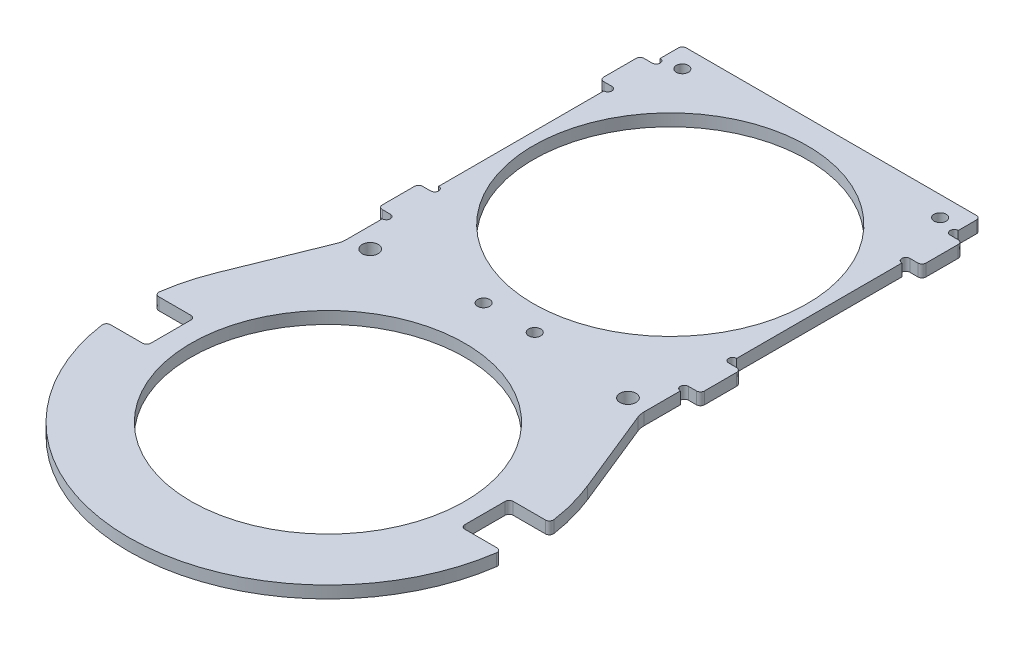
SolidWorks part; units mm, degrees
material "Thornel Mat VMA"
ref_plane "前视基准面" through (0, 0, 0) normal (0, 0, 1) x (1, 0, 0)
ref_plane "上视基准面" through (0, 0, 0) normal (0, 1, 0) x (1, 0, 0)
ref_plane "右视基准面" through (0, 0, 0) normal (1, 0, 0) x (0, 0, -1)
sketch "草图1" plane through (0, 0, 0) normal (0, 1, 0) x (1, 0, 0)
  line L8 (0, 85) -> (0, 0) construction
  line L9 (-6.35, 45) -> (6.35, 45) construction
  line L10 (-37, 40.5) -> (-37, 52.5)
  line L17 (0, -55) -> (0, 55) construction
  line L18 (37, 40.5) -> (37, 52.5)
  line L38 (-37, 125) -> (37, 125)
  line L39 (-37, 125) -> (-37, 117.5)
  line L40 (-37, 117.5) -> (-40, 117.5)
  line L41 (-40, 117.5) -> (-40, 107.5)
  line L42 (-40, 107.5) -> (-37, 107.5)
  line L43 (-37, 107.5) -> (-37, 62.5)
  line L44 (-37, 62.5) -> (-40, 62.5)
  line L45 (-40, 62.5) -> (-40, 52.5)
  line L46 (-40, 52.5) -> (-37, 52.5)
  line L47 (40, 52.5) -> (37, 52.5)
  line L48 (40, 62.5) -> (40, 52.5)
  line L49 (37, 62.5) -> (40, 62.5)
  line L50 (37, 107.5) -> (37, 62.5)
  line L51 (40, 107.5) -> (37, 107.5)
  line L52 (40, 117.5) -> (40, 107.5)
  line L53 (37, 117.5) -> (40, 117.5)
  line L54 (37, 125) -> (37, 117.5)
  line L55 (-45.8778, 18.5869) -> (-37, 40.5)
  line L56 (45.8778, 18.5869) -> (37, 40.5)
  circle A1 centre (-6.35, 45) radius 1.5
  circle A2 centre (6.35, 45) radius 1.5
  arc A7 (-45.8778, 18.5869) -> (45.8778, 18.5869) centre (0, 0) ccw
  circle A12 centre (0, 85) radius 34
  circle A14 centre (0, 0) radius 34
  circle A15 centre (-32, 120) radius 1.5
  circle A16 centre (-32, 42.5) radius 2
  circle A17 centre (32, 42.5) radius 2
  circle A18 centre (32, 120) radius 1.5
  point P10 (0, 45)
  dimension "D3" = 3
  dimension "D2" = 99
  dimension "D8" = 3
  dimension "D7" = 68
  dimension "D6" = 45
  dimension "D1" = 68
  dimension "D12" = 40
  dimension "D15" = 4
  dimension "D16" = 42.5
  dimension "D17" = 64
  dimension "D10" = 45
  dimension "D18" = 5
  dimension "D19" = 5
  dimension "D20" = 3
  dimension "D4" = 85
  dimension "D5" = 12.7
  dimension "D9" = 10
  dimension "D11" = 7.5
  dimension "D13" = 74
  dimension "D14" = 12
extrude "凸台-拉伸1" add sketch "草图1" along normal blind 3
sketch "草图2" plane through (0, 3, 0) normal (0, 1, 0) x (1, 0, 0)
  line L1 (-49.135, 6) -> (-39, 6)
  line L7 (-49.135, -6) -> (-39, -6)
  line L12 (-39, 6) -> (-39, -6)
  line L28 (49.135, 6) -> (39, 6)
  line L32 (49.135, -6) -> (39, -6)
  line L35 (39, 6) -> (39, -6)
  arc A47 (-45.8778, 18.5869) -> (45.8778, 18.5869) centre (0, 0) ccw construction
  arc A50 (-49.135, 6) -> (-49.135, -6) centre (0, 0) ccw
  arc A51 (49.135, -6) -> (49.135, 6) centre (0, 0) ccw
  dimension "D2" = 78
  dimension "D1" = 12
extrude "切除-拉伸1" cut sketch "草图2" against normal through all
sketch "草图8" plane through (0, 3, 0) normal (0, 1, 0) x (1, 0, 0)
  line L3 (-37, 125) -> (-37, 117.5) construction
  line L12 (-37, 107.5) -> (-37, 62.5) construction
  line L13 (-37, 52.5) -> (-37, 40.5) construction
  line L14 (0, -1.65) -> (0, 1.65) construction
  circle A0 centre (-37, 118.5) radius 1
  circle A54 centre (-37, 106.5) radius 1
  circle A55 centre (-37, 63.5) radius 1
  circle A64 centre (-37, 51.5) radius 1
  circle A77 centre (37, 51.5) radius 1
  circle A78 centre (37, 63.5) radius 1
  circle A79 centre (37, 106.5) radius 1
  circle A80 centre (37, 118.5) radius 1
  dimension "D1" = 2
extrude "切除-拉伸3" cut sketch "草图8" against normal through all
sketch "草图9" [suppressed] plane through (0, 3, 0) normal (0, 1, 0) x (1, 0, 0)
  line L0 (-67.5, 27) -> (-110, 56)
  line L1 (-110, 27) -> (-67.5, 56)
  line L2 (-107.5, 9) -> (-62.5, -9)
  line L3 (-107.5, -9) -> (-62.5, 9)
  line L5 (92.5, 17) -> (62.5, -1)
  line L7 (110, 27) -> (67.5, 49.0204)
  line L8 (67.5, 27) -> (110, 49.0204)
extrude "拉伸-薄壁1" [suppressed] add sketch "草图9" against normal up to surface (3 mm away) thin
sketch "草图10" [suppressed] plane through (0, 3, 0) normal (0, 1, 0) x (1, 0, 0)
  line L0 (-135, 65.8183) -> (-57.2183, 143.6001)
  line L1 (-57.2183, 143.6001) -> (-54.1292, 140.511)
  line L2 (-78.4116, 122.4067) -> (-135, 65.8183) construction
  line L3 (-135, 65.8183) -> (-54.1292, 140.511)
  line L4 (0, -1.65) -> (0, 1.65) construction
  line L5 (135, 65.8183) -> (57.2183, 143.6001)
  line L6 (57.2183, 143.6001) -> (54.1292, 140.511)
  line L7 (135, 65.8183) -> (54.1292, 140.511)
  arc A0 (-15.4534, 152.552) -> (-78.4116, 122.4067) centre (-4.1654, 48.1605) ccw construction
  dimension "D1" = 110
extrude "凸台-拉伸5" [suppressed] add sketch "草图10" against normal blind 3
sketch "草图11" [suppressed] plane through (0, 3, 0) normal (0, 1, 0) x (1, 0, 0)
  line L0 (-57.2183, 143.6001) -> (-71.3604, 129.4579)
  line L1 (-57.2183, 143.6001) -> (-59.3396, 145.7214)
  line L2 (-71.3604, 129.4579) -> (-73.4817, 131.5793)
  line L3 (-59.3396, 145.7214) -> (-73.4817, 131.5793)
  line L4 (-57.2183, 143.6001) -> (-135, 65.8183) construction
  line L5 (-135, 65.8183) -> (-120.9286, 79.8898)
  line L6 (-135, 65.8183) -> (-137.1213, 67.9396)
  line L7 (-120.9286, 79.8898) -> (-123.0499, 82.0111)
  line L8 (-137.1213, 67.9396) -> (-123.0499, 82.0111)
  line L9 (-99.7154, 101.103) -> (-82.0377, 118.7806)
  line L10 (-99.7154, 101.103) -> (-101.8367, 103.2243)
  line L11 (-82.0377, 118.7806) -> (-84.159, 120.9019)
  line L12 (-101.8367, 103.2243) -> (-84.159, 120.9019)
  line L13 (0, -1.65) -> (0, 1.65) construction
  line L14 (101.8367, 103.2243) -> (84.159, 120.9019)
  line L15 (82.0377, 118.7806) -> (84.159, 120.9019)
  line L16 (99.7154, 101.103) -> (101.8367, 103.2243)
  line L17 (99.7154, 101.103) -> (82.0377, 118.7806)
  line L18 (137.1213, 67.9396) -> (123.0499, 82.0111)
  line L19 (120.9286, 79.8898) -> (123.0499, 82.0111)
  line L20 (135, 65.8183) -> (137.1213, 67.9396)
  line L21 (135, 65.8183) -> (120.9286, 79.8898)
  line L22 (59.3396, 145.7214) -> (73.4817, 131.5793)
  line L23 (71.3604, 129.4579) -> (73.4817, 131.5793)
  line L24 (57.2183, 143.6001) -> (59.3396, 145.7214)
  line L25 (57.2183, 143.6001) -> (71.3604, 129.4579)
  dimension "D1" = 3
  dimension "D2" = 20
  dimension "D3" = 19.9
  dimension "D4" = 15.1
  dimension "D5" = 30
extrude "凸台-拉伸6" [suppressed] add sketch "草图11" against normal blind 3
sketch "草图12" [suppressed] plane through (0, 3, 0) normal (0, 1, 0) x (1, 0, 0)
  line L0 (-97.5, 40.8183) -> (-97.5, 44.8183) construction
  line L5 (-135, 40.8183) -> (-60, 40.8183) construction
  line L6 (0, -1.65) -> (0, 1.65) construction
  line L7 (-112.5, 45.8183) -> (-82.5, 45.8183)
  line L8 (-112.5, 45.8183) -> (-112.5, 43.8183)
  line L9 (-112.5, 43.8183) -> (-82.5, 43.8183)
  line L10 (-82.5, 45.8183) -> (-82.5, 43.8183)
  line L11 (-112.5, 45.8183) -> (-82.5, 43.8183) construction
  line L12 (-112.5, 43.8183) -> (-82.5, 45.8183) construction
  line L13 (112.5, 43.8183) -> (82.5, 43.8183)
  line L14 (82.5, 45.8183) -> (82.5, 43.8183)
  line L15 (112.5, 45.8183) -> (82.5, 45.8183)
  line L16 (112.5, 45.8183) -> (112.5, 43.8183)
  dimension "D1" = 3
  dimension "D2" = 2
  dimension "D3" = 30
extrude "切除-拉伸4" [suppressed] cut sketch "草图12" against normal blind 10
sketch "草图13" [suppressed] plane through (0, 3, 0) normal (0, 1, 0) x (1, 0, 0)
  line L0 (-71.3604, 129.4579) -> (-82.0377, 118.7806) construction
  line L1 (-99.7154, 101.103) -> (-120.9286, 79.8898) construction
  line L2 (-82.5, 45.8183) -> (-112.5, 45.8183) construction
  line L3 (-112.5, 43.8183) -> (-82.5, 43.8183) construction
  line L4 (0, -1.65) -> (0, 1.65) construction
  circle A0 centre (-71.9968, 128.8215) radius 0.9
  circle A1 centre (-81.4013, 119.417) radius 0.9
  circle A2 centre (-100.3518, 100.4666) radius 0.9
  circle A3 centre (-120.2922, 80.5261) radius 0.9
  circle A4 centre (-111.6, 45.8183) radius 0.9
  circle A5 centre (-111.6, 43.8183) radius 0.9
  circle A6 centre (-83.4, 45.8183) radius 0.9
  circle A7 centre (-83.4, 43.8183) radius 0.9
  circle A8 centre (83.4, 43.8183) radius 0.9
  circle A9 centre (83.4, 45.8183) radius 0.9
  circle A10 centre (111.6, 43.8183) radius 0.9
  circle A11 centre (111.6, 45.8183) radius 0.9
  circle A12 centre (120.2922, 80.5261) radius 0.9
  circle A13 centre (100.3518, 100.4666) radius 0.9
  circle A14 centre (81.4013, 119.417) radius 0.9
  circle A15 centre (71.9968, 128.8215) radius 0.9
  dimension "D1" = 1.8
extrude "切除-拉伸5" [suppressed] cut sketch "草图13" against normal through all
fillet "圆角1" radius 1 18 edges at (49.135, 1.5, 6) (39, 1.5, 6) (49.135, 1.5, -6) (39, 1.5, -6) (-49.135, 1.5, 6) (-39, 1.5, 6) (-39, 1.5, -6) (-49.135, 1.5, -6) (-37, 1.5, -125) (37, 1.5, -125) (40, 1.5, -117.5) (40, 1.5, -107.5) (40, 1.5, -62.5) (40, 1.5, -52.5) (-40, 1.5, -52.5) (-40, 1.5, -62.5) (-40, 1.5, -107.5) (-40, 1.5, -117.5)
fillet "圆角2" radius 5 2 edges at (-37, 1.5, -40.5) (37, 1.5, -40.5)
